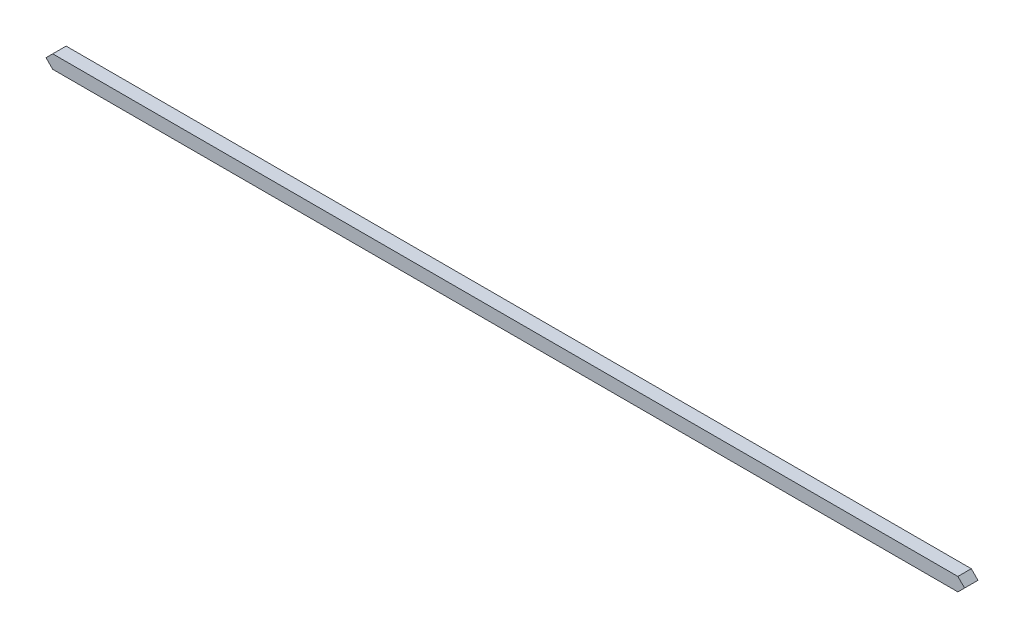
SolidWorks part; units mm, degrees
ref_plane "Front Plane" through (0, 0, 0) normal (0, 0, 1) x (1, 0, 0)
ref_plane "Top Plane" through (0, 0, 0) normal (0, 1, 0) x (1, 0, 0)
ref_plane "Right Plane" through (0, 0, 0) normal (1, 0, 0) x (0, 0, -1)
sketch "Sketch2" plane through (0, 0, 0) normal (0, 0, 1) x (1, 0, 0)
  line L0 (-1370, 0) -> (-1350, 20)
  line L1 (55, 0) -> (-55, 0) construction
  line L4 (0, -55) -> (0, 55) construction
  line L6 (1370, 0) -> (1350, 20)
  line L8 (-1350, 20) -> (1350, 20)
  line L10 (-1370, 0) -> (-1350, -20)
  line L11 (-1350, -20) -> (1350, -20)
  line L12 (1370, 0) -> (1350, -20)
  dimension "D1" = 40
  dimension "D2" = 90
  dimension "D3" = 2700
extrude "Boss-Extrude1" add sketch "Sketch2" along normal blind 40
